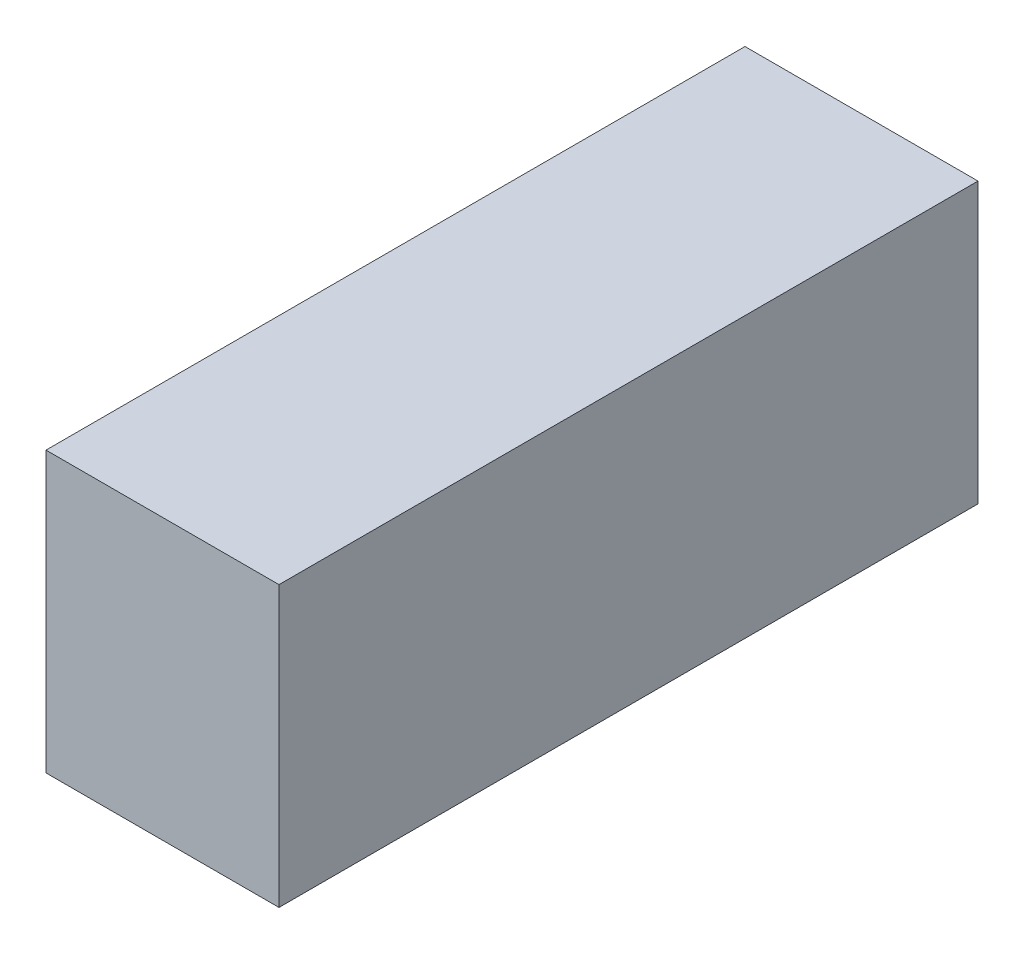
SolidWorks part; units mm, degrees
material "普通碳钢"
ref_plane "前视基准面" through (0, 0, 0) normal (0, 0, 1) x (1, 0, 0)
ref_plane "上视基准面" through (0, 0, 0) normal (0, 1, 0) x (1, 0, 0)
ref_plane "右视基准面" through (0, 0, 0) normal (1, 0, 0) x (0, 0, -1)
sketch "草图1" plane through (0, 0, 0) normal (0, 0, 1) x (1, 0, 0)
  line L1 (-0.25, 0.3) -> (0.25, 0.3)
  line L2 (-0.25, 0.3) -> (-0.25, -0.3)
  line L3 (-0.25, -0.3) -> (0.25, -0.3)
  line L4 (0.25, 0.3) -> (0.25, -0.3)
  line L5 (-0.25, 0.3) -> (0.25, -0.3) construction
  line L6 (-0.25, -0.3) -> (0.25, 0.3) construction
  point P0 (0, 0)
extrude "凸台-拉伸1" add sketch "草图1" along normal blind 1.5
